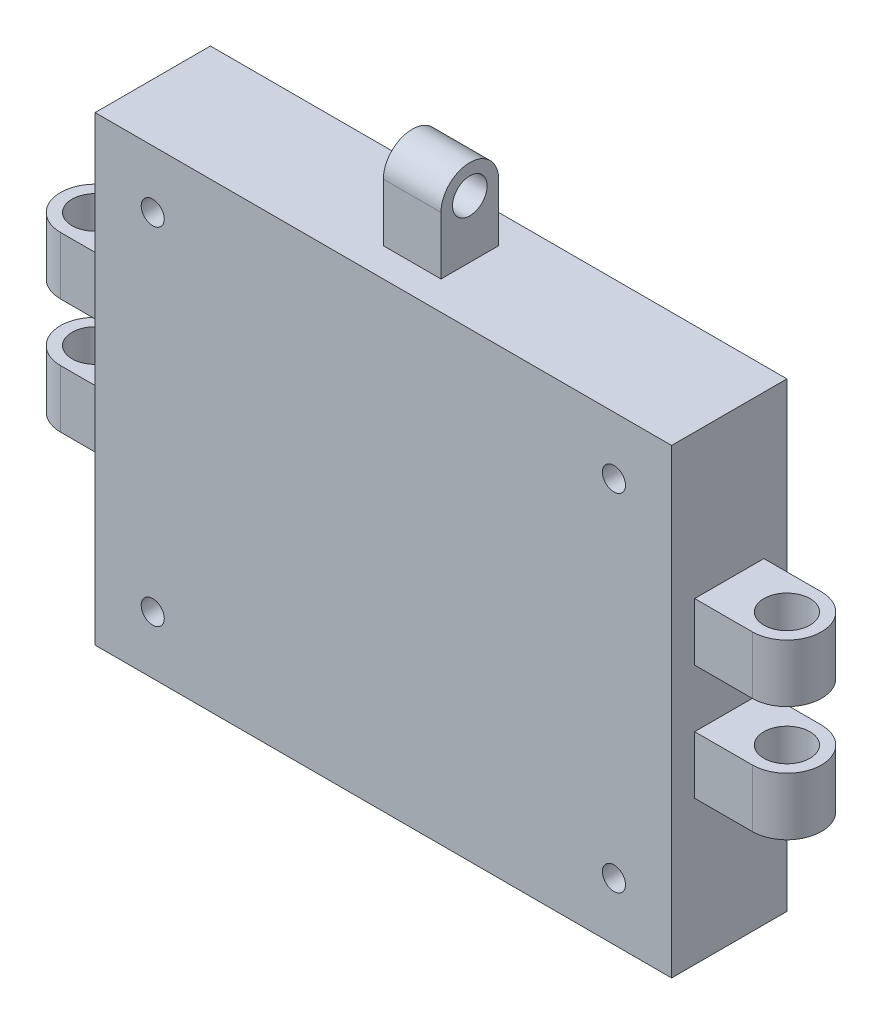
SolidWorks part; units mm, degrees
ref_plane "Front Plane" through (0, 0, 0) normal (0, 0, 1) x (1, 0, 0)
ref_plane "Top Plane" through (0, 0, 0) normal (0, 1, 0) x (1, 0, 0)
ref_plane "Right Plane" through (0, 0, 0) normal (1, 0, 0) x (0, 0, -1)
sketch "Sketch1" plane through (669.8418, 0, 0) normal (0, 0, 1) x (1, 0, 0)
  line L1 (-696.3103, 457.6379) -> (-646.3103, 457.6379)
  line L2 (-696.3103, 457.6379) -> (-696.3103, 417.6379)
  line L3 (-696.3103, 417.6379) -> (-646.3103, 417.6379)
  line L4 (-646.3103, 457.6379) -> (-646.3103, 417.6379)
  dimension "50" = 50
  dimension "D2" = 40
extrude "Boss-Extrude1" add sketch "Sketch1" along normal blind 10
sketch "Sketch5" plane through (23.5315, 0, 0) normal (1, 0, 0) x (0, 0, -1)
  line L0 (0, 417.6379) -> (0, 457.6379) construction
  line L1 (-8, 445.1379) -> (-2, 445.1379)
  line L2 (-8, 445.1379) -> (-8, 440.1379)
  line L3 (-8, 440.1379) -> (-2, 440.1379)
  line L4 (-2, 445.1379) -> (-2, 440.1379)
  line L5 (-8, 435.1379) -> (-2, 435.1379)
  line L6 (-8, 435.1379) -> (-8, 430.1379)
  line L7 (-8, 430.1379) -> (-2, 430.1379)
  line L8 (-2, 435.1379) -> (-2, 430.1379)
  line L9 (-10, 417.6379) -> (-10, 457.6379) construction
  line L10 (0, 437.6379) -> (-10, 437.6379)
  line L11 (-2, 440.1379) -> (-2, 437.6379)
  line L12 (-8, 435.1379) -> (-8, 437.6379)
  dimension "D1" = 5
  dimension "D2" = 2
  dimension "D3" = 2
  dimension "D4" = 2
  dimension "D5" = 2
  dimension "D6" = 5
  dimension "D7" = 5
extrude "Boss-Extrude3" add sketch "Sketch5" along normal blind 10 contours L4 L1 L2 L3 | L8 L5 L6 L7
sketch "Sketch6" plane through (669.8418, 445.1379, 0) normal (0, 1, 0) x (1, 0, 0)
  line L1 (-646.3103, -8) -> (-646.3103, -2) construction
  line L2 (-646.3103, -5) -> (-636.3103, -5) construction
  line L3 (-636.3103, -8) -> (-636.3103, -2) construction
  line L4 (-641.3103, -8) -> (-641.3103, -2) construction
  line L5 (-636.3103, -8) -> (-646.3103, -8) construction
  line L6 (-636.3103, -2) -> (-646.3103, -2) construction
  circle A1 centre (-641.3103, -5) radius 2
extrude "Cut-Extrude1" cut sketch "Sketch6" against normal blind 20
sketch "Sketch8" plane through (-26.4685, 0, 0) normal (-1, 0, 0) x (0, 0, 1)
  line L1 (0, 417.6379) -> (10, 417.6379)
  line L2 (0, 417.6379) -> (0, 457.6379)
  line L3 (0, 457.6379) -> (10, 457.6379)
  line L4 (10, 417.6379) -> (10, 457.6379)
extrude "Cut-Extrude2" cut sketch "Sketch8" against normal blind 25
mirror "Mirror1" about plane through (-1.4685, 0, 0) normal (1, 0, 0) of "Cut-Extrude1", "Boss-Extrude1", "Boss-Extrude3"
sketch "Sketch9" plane through (0, 435.1379, 0) normal (0, 1, 0) x (1, 0, 0)
  line L1 (23.5315, -8) -> (33.5315, -8)
  line L2 (23.5315, -8) -> (23.5315, -2)
  line L3 (23.5315, -2) -> (33.5315, -2)
  line L4 (33.5315, -8) -> (33.5315, -2)
  circle A0 centre (28.5315, -5) radius 1.9309
sketch "Sketch12" plane through (0, 457.6379, 0) normal (0, 1, 0) x (1, 0, 0)
  line L0 (23.5315, 0) -> (-26.4685, 0) construction
  line L1 (-3.9685, -2.5) -> (1.0315, -2.5)
  line L2 (-3.9685, -2.5) -> (-3.9685, -7.5)
  line L3 (-3.9685, -7.5) -> (1.0315, -7.5)
  line L4 (1.0315, -2.5) -> (1.0315, -7.5)
  line L5 (23.5315, -10) -> (-26.4685, -10) construction
  line L6 (23.5315, -10) -> (23.5315, 0) construction
  line L7 (-26.4685, -10) -> (-26.4685, 0) construction
  dimension "D1" = 2.5
  dimension "D2" = 2.5
  dimension "D3" = 22.5
  dimension "D4" = 22.5
extrude "Boss-Extrude5" add sketch "Sketch12" along normal blind 10
sketch "Sketch13" plane through (1.0315, 0, 0) normal (1, 0, 0) x (0, 0, -1)
  line L0 (-5, 467.6379) -> (-5, 457.6379) construction
  line L1 (-7.5, 467.6379) -> (-2.5, 467.6379) construction
  line L2 (-7.5, 457.6379) -> (-2.5, 457.6379) construction
  line L3 (-7.5, 462.6379) -> (-2.5, 462.6379) construction
  line L4 (-7.5, 467.6379) -> (-7.5, 457.6379) construction
  line L5 (-2.5, 467.6379) -> (-2.5, 457.6379) construction
  circle A1 centre (-5, 462.6379) radius 1.5
extrude "Cut-Extrude4" cut sketch "Sketch13" against normal blind 10
sketch "Sketch14" plane through (0, 0, 10) normal (0, 0, 1) x (1, 0, 0)
  line L0 (23.5315, 457.6379) -> (-26.4685, 457.6379) construction
  line L1 (23.5315, 417.6379) -> (23.5315, 457.6379) construction
  line L2 (-26.4685, 417.6379) -> (-26.4685, 457.6379) construction
  line L3 (-26.4685, 417.6379) -> (23.5315, 417.6379) construction
  circle A0 centre (-21.4685, 452.6379) radius 1
  circle A1 centre (-21.4685, 422.6379) radius 1
  circle A2 centre (18.5315, 452.6379) radius 1
  circle A3 centre (18.5315, 422.6379) radius 1
  point P8 (0, 0)
  point P9 (0, 0)
  point P10 (0, 0)
  point P11 (0, 0)
  point P12 (19.7159, 454.1304)
  point P13 (0, 0)
  point P14 (0, 0)
  point P15 (-24.376, 420.1968)
  point P16 (21.1586, 454.9662)
  point P21 (21.8607, 452.4781)
  point P22 (-22.4589, 452.6379)
  dimension "D1" = 2
  dimension "D4" = 5
  dimension "D2" = 5
  dimension "D3" = 5
  dimension "D5" = 5
extrude "Cut-Extrude5" cut sketch "Sketch14" against normal blind 10
sketch "Sketch15" plane through (0, 445.1379, 0) normal (0, 1, 0) x (1, 0, 0)
  line L0 (28.5315, -2) -> (33.5315, -2)
  line L1 (28.5315, -8) -> (33.5315, -8)
  circle A0 centre (28.5315, -5) radius 3
  line M3 (23.5315, -8) -> (33.5315, -8)
  line M4 (33.5315, -8) -> (33.5315, -2)
  line M5 (33.5315, -2) -> (23.5315, -2)
extrude "Cut-Extrude6" cut sketch "Sketch15" against normal blind 22 contours A0 M3 M4 M5
sketch "Sketch17" plane through (0, 445.1379, 0) normal (0, 1, 0) x (1, 0, 0)
  line L0 (-31.4685, -8) -> (-36.4685, -8)
  line L1 (-36.4685, -8) -> (-36.4685, -2)
  line L2 (-36.4685, -2) -> (-31.4685, -2)
  circle A0 centre (-31.4685, -5) radius 3
  line M3 (-26.4685, -2) -> (-36.4685, -2)
  line M4 (-36.4685, -2) -> (-36.4685, -8)
  line M5 (-36.4685, -8) -> (-26.4685, -8)
extrude "Cut-Extrude7" cut sketch "Sketch17" against normal blind 30 contours A0 M3 M4 M5
sketch "Sketch18" plane through (1.0315, 0, 0) normal (1, 0, 0) x (0, 0, -1)
  line L0 (-7.5, 462.6379) -> (-7.5, 467.6379)
  line L1 (-7.5, 467.6379) -> (-2.5, 467.6379)
  line L2 (-2.5, 467.6379) -> (-2.5, 462.6379)
  circle A0 centre (-5, 462.6379) radius 2.5
  line M4 (-2.5, 457.6379) -> (-2.5, 467.6379)
  line M5 (-2.5, 467.6379) -> (-7.5, 467.6379)
  line M6 (-7.5, 467.6379) -> (-7.5, 457.6379)
extrude "Cut-Extrude8" cut sketch "Sketch18" against normal blind 30 contours A0 M4 M5 M6
